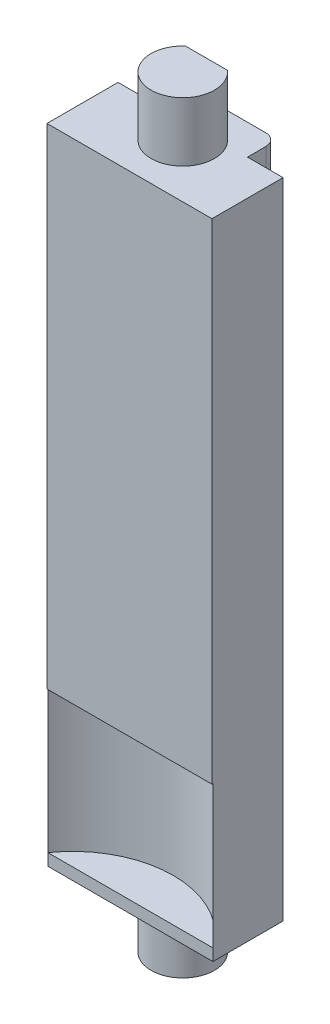
SolidWorks part; units mm, degrees
ref_plane "Front Plane" through (0, 0, 0) normal (0, 0, 1) x (1, 0, 0)
ref_plane "Top Plane" through (0, 0, 0) normal (0, 1, 0) x (1, 0, 0)
ref_plane "Right Plane" through (0, 0, 0) normal (1, 0, 0) x (0, 0, -1)
sketch "Sketch1" plane through (0, 0, 0) normal (0, 1, 0) x (1, 0, 0)
  line L0 (0, -2.55) -> (-3, -2.55)
  line L1 (0, 0) -> (7.92, 0)
  line L2 (0, 0) -> (0, -2.55)
  line L3 (0, -2.55) -> (7.92, -2.55)
  line L4 (7.92, 0) -> (7.92, -2.55)
  line L5 (-3, -8.55) -> (10.92, -8.55)
  line L6 (-3, -2.55) -> (-3, -8.55)
  line L7 (10.92, -8.55) -> (10.92, -2.55)
  line L8 (10.92, -2.55) -> (7.92, -2.55)
  point P5 (3.96, -2.55)
  dimension "D1" = 7.92
  dimension "D2" = 2.55
  dimension "D3" = 6
  dimension "D4" = 3
extrude "Boss-Extrude1" add sketch "Sketch1" along normal blind 54.32
fillet "Fillet1" radius 1 2 edges at (7.92, 27.16, 0) (0, 27.16, 0)
sketch "Sketch2" plane through (0, 54.32, 0) normal (0, 1, 0) x (1, 0, 0)
  line L1 (10.92, -2.55) -> (7.92, -2.55) construction
  line L3 (1, 0) -> (6.92, 0) construction
  line L4 (2.1836, -2.05) -> (5.7364, -2.05)
  circle A0 centre (3.96, -4.05) radius 2.675
  point P1 (3.96, -4.05)
  point P4 (3.96, 0)
  point P5 (3.96, -3.55)
  dimension "D1" = 5.35
  dimension "D2" = 1.5
  dimension "D3" = 2
extrude "Boss-Extrude2" add sketch "Sketch2" along normal blind 5 contours L4 A0
ref_plane "Plane1" through (0, 27.16, 0) normal (0, 1, 0) x (1, 0, 0)
mirror "Mirror1" about plane through (0, 27.16, 0) normal (0, 1, 0) of "Boss-Extrude2"
ref_plane "Plane2" through (0, 0, 0) normal (0, -1, 0) x (-1, 0, 0)
sketch "Sketch3" plane through (0, 0, 0) normal (0, -1, 0) x (1, 0, 0)
  line L0 (1, 0) -> (6.92, 0) construction
  circle A3 centre (3.96, 13.3485) radius 8.5
  point P2 (3.96, 0)
  point P3 (0, 0)
  dimension "D1" = 17
extrude "Cut-Extrude1" cut sketch "Sketch3" against normal blind 13
sketch "Sketch4" plane through (0, 0, 0) normal (0, 1, 0) x (1, 0, 0)
  line L0 (-3, -8.4691) -> (10.92, -8.4691)
  arc A0 (6.3757, -5.199) -> (1.5443, -5.199) centre (3.96, -13.3485) ccw construction
  arc A2 (6.3757, -5.199) -> (1.5443, -5.199) centre (3.96, -13.3485) ccw
  arc A3 (1.5443, -5.199) -> (-3, -8.4691) centre (3.96, -13.3485) ccw construction
  arc A4 (10.92, -8.4691) -> (6.3757, -5.199) centre (3.96, -13.3485) ccw construction
  arc A5 (1.5443, -5.199) -> (-3, -8.4691) centre (3.96, -13.3485) ccw
  arc A6 (10.92, -8.4691) -> (6.3757, -5.199) centre (3.96, -13.3485) ccw
extrude "Boss-Extrude3" add sketch "Sketch4" along normal blind 1
